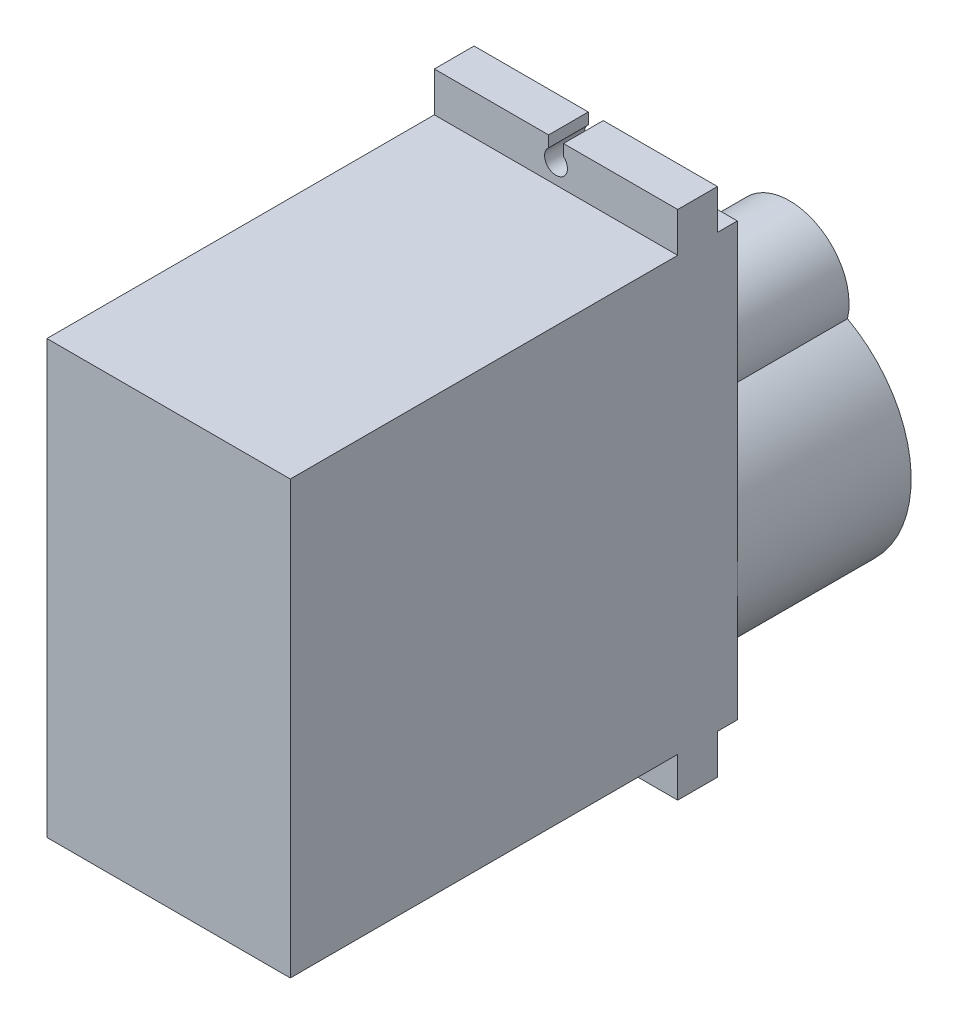
SolidWorks part; units mm, degrees
ref_plane "Front Plane" through (0, 0, 0) normal (0, 0, 1) x (1, 0, 0)
ref_plane "Top Plane" through (0, 0, 0) normal (0, 1, 0) x (1, 0, 0)
ref_plane "Right Plane" through (0, 0, 0) normal (1, 0, 0) x (0, 0, -1)
sketch "Sketch1" plane through (0, 0, 0) normal (0, 0, 1) x (1, 0, 0)
  line L1 (6.223, -11.049) -> (-6.223, -11.049)
  line L2 (6.223, -11.049) -> (6.223, 11.049)
  line L3 (6.223, 11.049) -> (-6.223, 11.049)
  line L4 (-6.223, -11.049) -> (-6.223, 11.049)
  line L5 (6.223, -11.049) -> (-6.223, 11.049) construction
  line L6 (6.223, 11.049) -> (-6.223, -11.049) construction
  point P0 (0, 0)
  dimension "D1" = 12.446
  dimension "D2" = 22.098
extrude "Boss-Extrude1" add sketch "Sketch1" along normal blind 22.86
sketch "Sketch2" plane through (0, 11.049, 0) normal (0, 1, 0) x (1, 0, 0)
  line L0 (-6.223, -22.86) -> (-6.223, 0) construction
  line L1 (6.223, -3.048) -> (-6.223, -3.048)
  line L2 (6.223, -3.048) -> (6.223, -1.016)
  line L3 (6.223, -1.016) -> (-6.223, -1.016)
  line L4 (-6.223, -3.048) -> (-6.223, -1.016)
  line L5 (6.223, -3.048) -> (-6.223, -1.016) construction
  line L6 (6.223, -1.016) -> (-6.223, -3.048) construction
  line L7 (6.223, 0) -> (-6.223, 0) construction
  point P0 (0, -2.032)
  dimension "D1" = 1.016
  dimension "D2" = 2.032
extrude "Boss-Extrude2" add sketch "Sketch2" along normal blind 2.032
sketch "Sketch3" plane through (0, 0, 1.016) normal (0, 0, -1) x (-1, 0, 0)
  line L0 (0, 13.081) -> (0, 11.049) construction
  line L1 (-6.223, 13.081) -> (6.223, 13.081) construction
  line L2 (-6.223, 11.049) -> (6.223, 11.049) construction
  line L3 (-0.381, 13.081) -> (-0.381, 12.5079)
  line L4 (0.381, 13.081) -> (0.381, 12.5079)
  line L5 (0, 12.065) -> (0.9393, 12.065) construction
  line L6 (-0.381, 13.081) -> (0.381, 13.081)
  arc A0 (-0.381, 12.5079) -> (0.381, 12.5079) centre (0, 12.065) ccw
  dimension "D3" = 0.5842
  dimension "D1" = 0.381
  dimension "D2" = 0.381
extrude "Cut-Extrude1" cut sketch "Sketch3" against normal blind 2.032
mirror "Mirror1" about plane through (0, 0, 0) normal (0, 1, 0) of "Boss-Extrude2"
mirror "Mirror2" about plane through (0, 0, 0) normal (0, 1, 0) of "Cut-Extrude1"
sketch "Sketch4" plane through (0, 0, 0) normal (0, 0, -1) x (-1, 0, 0)
  line L0 (6.223, -11.049) -> (-6.223, -11.049) construction
  line L1 (6.223, 11.049) -> (6.223, -11.049) construction
  line L2 (-6.223, -11.049) -> (-6.223, 11.049) construction
  arc A0 (-2.9671, 0.6441) -> (2.9671, 0.6441) centre (0, -4.826) ccw
  arc A1 (-2.9671, 0.6441) -> (2.9671, 0.6441) centre (0, 1.3415) cw
  dimension "D1" = 3.048
  dimension "D2" = 2.9671
extrude "Boss-Extrude3" add sketch "Sketch4" along normal blind 8.89
sketch "Sketch5" plane through (0, 0, -8.89) normal (0, 0, -1) x (-1, 0, 0)
  circle A0 centre (0, -4.826) radius 2.54
  dimension "D1" = 5.08
extrude "Cut-Extrude2" cut sketch "Sketch5" against normal blind 1.27
